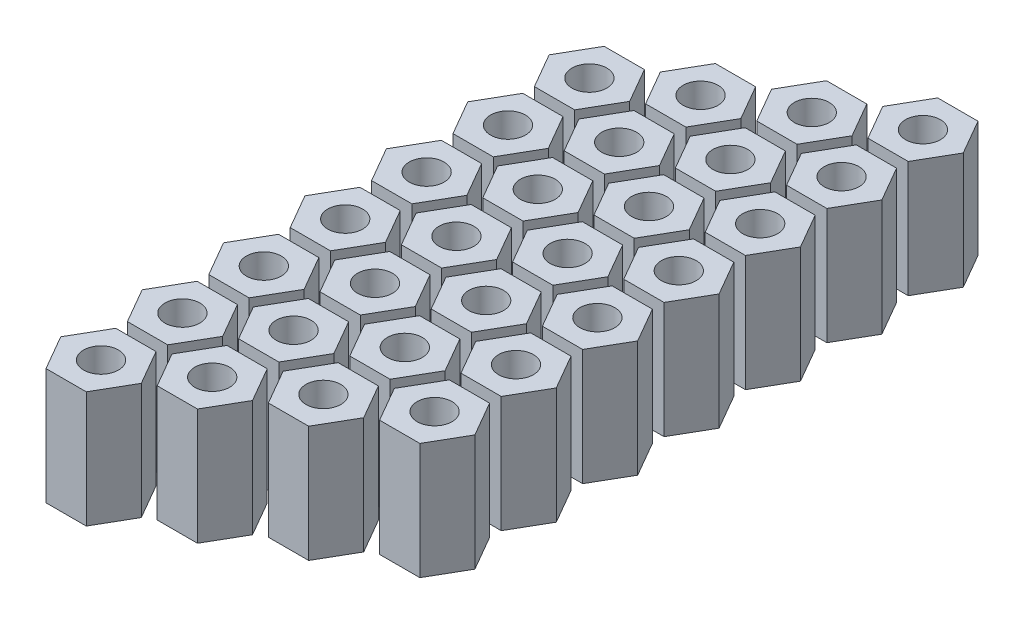
SolidWorks part; units mm, degrees
ref_plane "Front Plane" through (0, 0, 0) normal (0, 0, 1) x (1, 0, 0)
ref_plane "Top Plane" through (0, 0, 0) normal (0, 1, 0) x (1, 0, 0)
ref_plane "Right Plane" through (0, 0, 0) normal (1, 0, 0) x (0, 0, -1)
sketch "Sketch1" plane through (0, 0, 0) normal (0, 1, 0) x (1, 0, 0)
  line L0 (0, 0) -> (3.4641, 0) construction
  line L1 (3.4641, 0) -> (1.7321, 3)
  line L2 (1.7321, 3) -> (-1.7321, 3)
  line L3 (-1.7321, 3) -> (-3.4641, 0)
  line L4 (-3.4641, 0) -> (-1.7321, -3)
  line L5 (-1.7321, -3) -> (1.7321, -3)
  line L6 (1.7321, -3) -> (3.4641, 0)
  circle A0 centre (0, 0) radius 3 construction
  circle A1 centre (0, 0) radius 1.5
  dimension "D2" = 3
  dimension "D1" = 6
extrude "Boss-Extrude1" add sketch "Sketch1" along normal blind 10
pattern_linear "LPattern1" count 7 spacing 7 along (0, 0, 1) count 4 spacing 7 along (-0.866, 0, 0.5) of bodies 101
